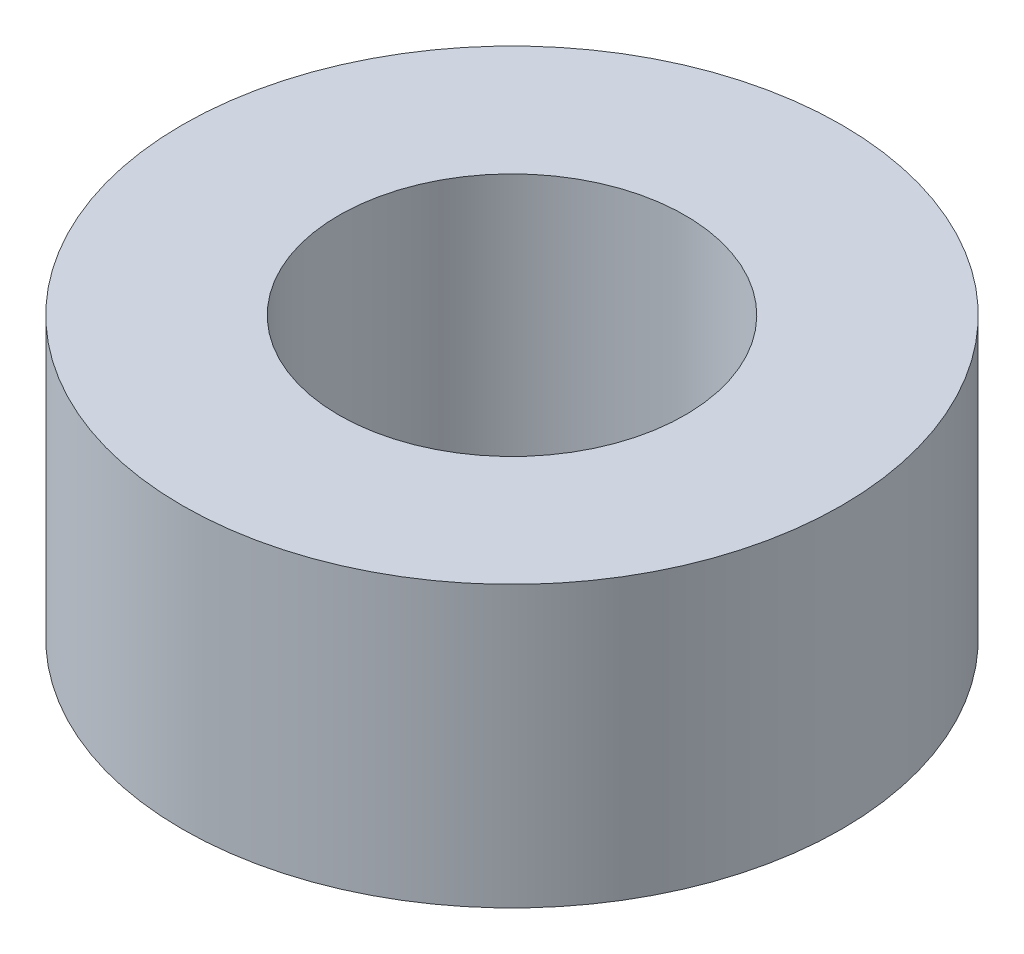
SolidWorks part; units mm, degrees
ref_plane "Front Plane" through (0, 0, 0) normal (0, 0, 1) x (1, 0, 0)
ref_plane "Top Plane" through (0, 0, 0) normal (0, 1, 0) x (1, 0, 0)
ref_plane "Right Plane" through (0, 0, 0) normal (1, 0, 0) x (0, 0, -1)
sketch "Sketch1" plane through (0, 0, 0) normal (0, 1, 0) x (1, 0, 0)
  circle A0 centre (0, 0) radius 12.7
  dimension "D1" = 25.4
extrude "Boss-Extrude1" add sketch "Sketch1" along normal blind 10.795 contours A0
sketch "Sketch4" plane through (0, 10.795, 0) normal (0, 1, 0) x (1, 0, 0)
  circle A0 centre (0, 0) radius 6.6675
  dimension "D1" = 13.335
extrude "Cut-Extrude1" cut sketch "Sketch4" against normal through all
sketch "Sketch5" plane through (0, 0, 0) normal (0, -1, 0) x (1, 0, 0)
